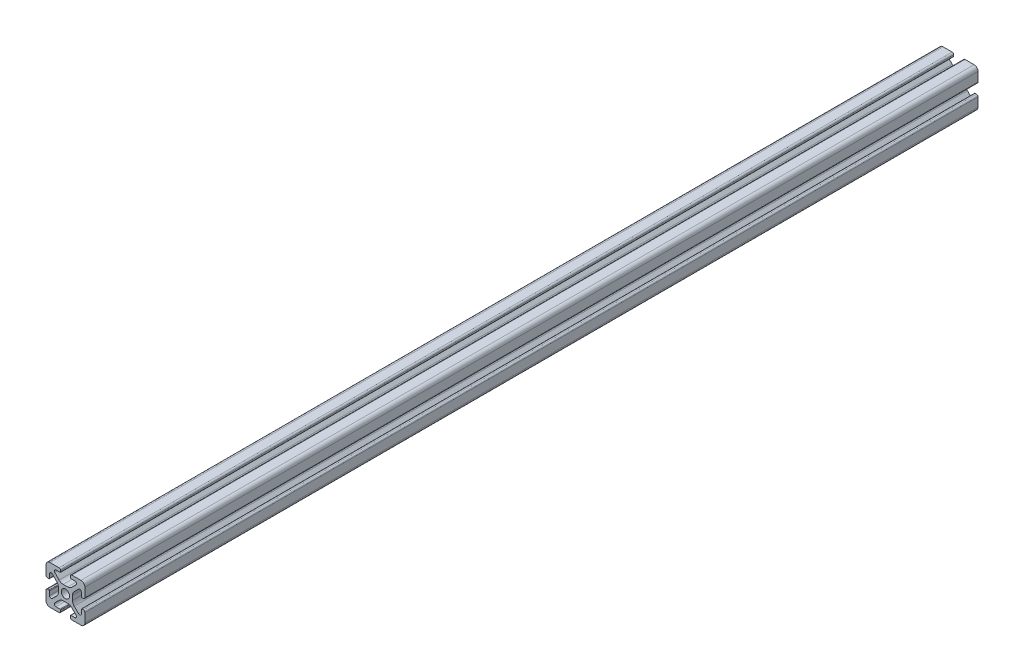
SolidWorks part; units mm, degrees
material "Alliage 1060"
ref_plane "Plan de face" through (0, 0, 0) normal (0, 0, 1) x (1, 0, 0)
ref_plane "Plan de dessus" through (0, 0, 0) normal (0, 1, 0) x (1, 0, 0)
ref_plane "Plan de droite" through (0, 0, 0) normal (1, 0, 0) x (0, 0, -1)
sketch "Esquisse1" plane through (0, 0, 0) normal (0, 0, 1) x (1, 0, 0)
  line L108 (-3.2559, 4.5287) -> (-5.5062, 6.779)
  line L109 (-4.9176, 8.2) -> (-2.8, 8.2)
  line L110 (-2.5, 8.5) -> (-2.5, 9.2)
  line L111 (-3.3, 10) -> (-8, 10)
  line L112 (-10, 8) -> (-10, 3.3)
  line L113 (-9.2, 2.5) -> (-8.5, 2.5)
  line L114 (-8.2, 2.8) -> (-8.2, 4.9176)
  line L115 (-6.779, 5.5062) -> (-4.5287, 3.2559)
  line L116 (-3.65, 1.1346) -> (-3.65, -1.1346)
  line L117 (-4.5287, -3.2559) -> (-6.779, -5.5062)
  line L118 (-8.2, -4.9176) -> (-8.2, -2.8)
  line L119 (-8.5, -2.5) -> (-9.2, -2.5)
  line L120 (-10, -3.3) -> (-10, -8)
  line L121 (-8, -10) -> (-3.3, -10)
  line L122 (-2.5, -9.2) -> (-2.5, -8.5)
  line L123 (-2.8, -8.2) -> (-4.9176, -8.2)
  line L124 (-5.5062, -6.779) -> (-3.2559, -4.5287)
  line L125 (-1.1346, -3.65) -> (1.1346, -3.65)
  line L126 (3.2559, -4.5287) -> (5.5062, -6.779)
  line L127 (4.9176, -8.2) -> (2.8, -8.2)
  line L128 (2.5, -8.5) -> (2.5, -9.2)
  line L129 (3.3, -10) -> (8, -10)
  line L130 (10, -8) -> (10, -3.3)
  line L131 (9.2, -2.5) -> (8.5, -2.5)
  line L132 (8.2, -2.8) -> (8.2, -4.9176)
  line L133 (6.779, -5.5062) -> (4.5287, -3.2559)
  line L134 (3.65, -1.1346) -> (3.65, 1.1346)
  line L135 (4.5287, 3.2559) -> (6.779, 5.5062)
  line L136 (8.2, 4.9176) -> (8.2, 2.8)
  line L137 (8.5, 2.5) -> (9.2, 2.5)
  line L138 (10, 3.3) -> (10, 8)
  line L139 (8, 10) -> (3.3, 10)
  line L140 (2.5, 9.2) -> (2.5, 8.5)
  line L141 (2.8, 8.2) -> (4.9176, 8.2)
  line L142 (5.5062, 6.779) -> (3.2559, 4.5287)
  line L143 (1.1346, 3.65) -> (-1.1346, 3.65)
  arc A42 (-2.15, 0) -> (2.15, 0) centre (0, 0) ccw
  arc A43 (2.15, 0) -> (-2.15, 0) centre (0, 0) ccw
  arc A108 (-4.9176, 8.2) -> (-5.5062, 6.779) centre (-4.9176, 7.3676) ccw
  arc A109 (-2.8, 8.2) -> (-2.5, 8.5) centre (-2.8, 8.5) ccw
  arc A110 (-2.5, 9.2) -> (-3.3, 10) centre (-3.3, 9.2) ccw
  arc A111 (-8, 10) -> (-10, 8) centre (-8, 8) ccw
  arc A112 (-10, 3.3) -> (-9.2, 2.5) centre (-9.2, 3.3) ccw
  arc A113 (-8.5, 2.5) -> (-8.2, 2.8) centre (-8.5, 2.8) ccw
  arc A114 (-6.779, 5.5062) -> (-8.2, 4.9176) centre (-7.3676, 4.9176) ccw
  arc A115 (-3.65, 1.1346) -> (-4.5287, 3.2559) centre (-6.65, 1.1346) ccw
  arc A116 (-4.5287, -3.2559) -> (-3.65, -1.1346) centre (-6.65, -1.1346) ccw
  arc A117 (-8.2, -4.9176) -> (-6.779, -5.5062) centre (-7.3676, -4.9176) ccw
  arc A118 (-8.2, -2.8) -> (-8.5, -2.5) centre (-8.5, -2.8) ccw
  arc A119 (-9.2, -2.5) -> (-10, -3.3) centre (-9.2, -3.3) ccw
  arc A120 (-10, -8) -> (-8, -10) centre (-8, -8) ccw
  arc A121 (-3.3, -10) -> (-2.5, -9.2) centre (-3.3, -9.2) ccw
  arc A122 (-2.5, -8.5) -> (-2.8, -8.2) centre (-2.8, -8.5) ccw
  arc A123 (-5.5062, -6.779) -> (-4.9176, -8.2) centre (-4.9176, -7.3676) ccw
  arc A124 (-1.1346, -3.65) -> (-3.2559, -4.5287) centre (-1.1346, -6.65) ccw
  arc A125 (3.2559, -4.5287) -> (1.1346, -3.65) centre (1.1346, -6.65) ccw
  arc A126 (4.9176, -8.2) -> (5.5062, -6.779) centre (4.9176, -7.3676) ccw
  arc A127 (2.8, -8.2) -> (2.5, -8.5) centre (2.8, -8.5) ccw
  arc A128 (2.5, -9.2) -> (3.3, -10) centre (3.3, -9.2) ccw
  arc A129 (8, -10) -> (10, -8) centre (8, -8) ccw
  arc A130 (10, -3.3) -> (9.2, -2.5) centre (9.2, -3.3) ccw
  arc A131 (8.5, -2.5) -> (8.2, -2.8) centre (8.5, -2.8) ccw
  arc A132 (6.779, -5.5062) -> (8.2, -4.9176) centre (7.3676, -4.9176) ccw
  arc A133 (3.65, -1.1346) -> (4.5287, -3.2559) centre (6.65, -1.1346) ccw
  arc A134 (4.5287, 3.2559) -> (3.65, 1.1346) centre (6.65, 1.1346) ccw
  arc A135 (8.2, 4.9176) -> (6.779, 5.5062) centre (7.3676, 4.9176) ccw
  arc A136 (8.2, 2.8) -> (8.5, 2.5) centre (8.5, 2.8) ccw
  arc A137 (9.2, 2.5) -> (10, 3.3) centre (9.2, 3.3) ccw
  arc A138 (10, 8) -> (8, 10) centre (8, 8) ccw
  arc A139 (3.3, 10) -> (2.5, 9.2) centre (3.3, 9.2) ccw
  arc A140 (2.5, 8.5) -> (2.8, 8.2) centre (2.8, 8.5) ccw
  arc A141 (5.5062, 6.779) -> (4.9176, 8.2) centre (4.9176, 7.3676) ccw
  arc A142 (1.1346, 3.65) -> (3.2559, 4.5287) centre (1.1346, 6.65) ccw
  arc A143 (-3.2559, 4.5287) -> (-1.1346, 3.65) centre (-1.1346, 6.65) ccw
extrude "Boss.-Extru.1" add sketch "Esquisse1" along normal blind 460
